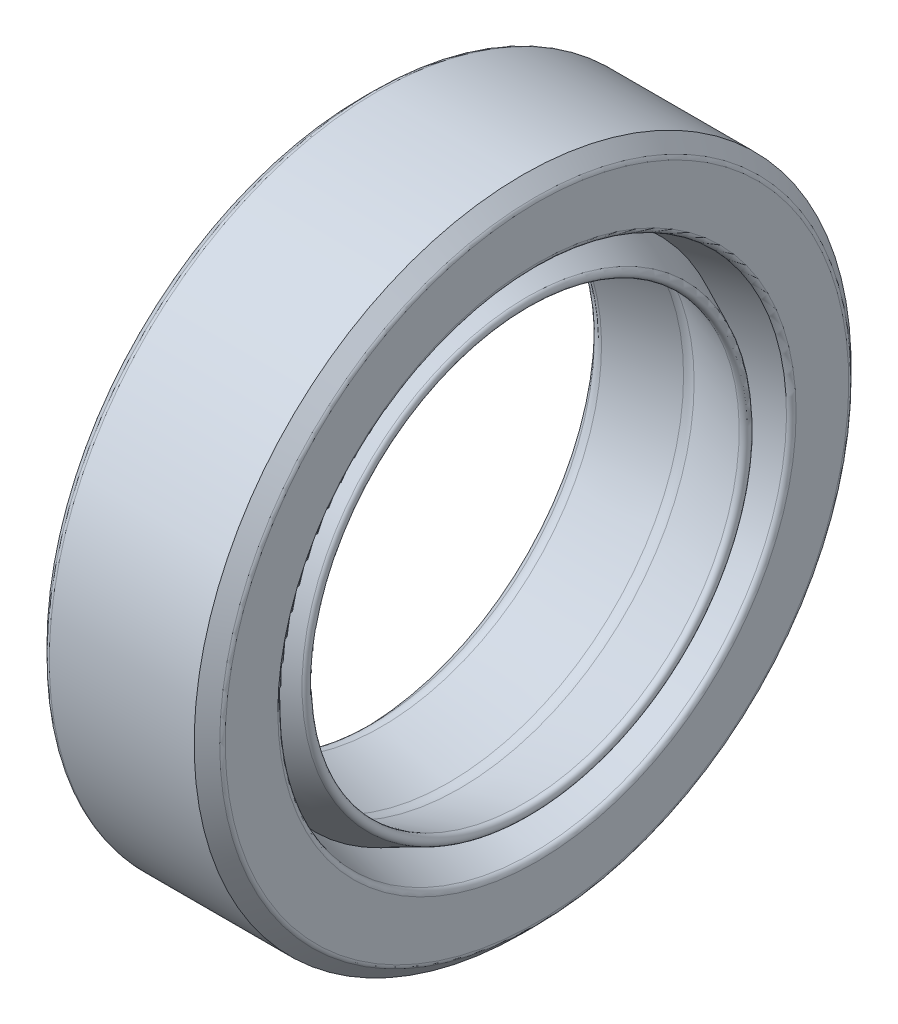
SolidWorks part; units mm, degrees
ref_plane "Front Plane" through (0, 0, 0) normal (0, 0, 1) x (1, 0, 0)
ref_plane "Top Plane" through (0, 0, 0) normal (0, 1, 0) x (1, 0, 0)
ref_plane "Right Plane" through (0, 0, 0) normal (1, 0, 0) x (0, 0, -1)
sketch "Sketch1" plane through (0, 0, 0) normal (0, 0, 1) x (1, 0, 0)
  line L0 (0, 0) -> (-7.6526, 0) construction
  line L2 (-6.8499, 12.3323) -> (-7.1853, 12.6677)
  line L3 (-7.2585, 12.8445) -> (-7.2585, 14.274)
  line L4 (-7.1853, 14.4508) -> (-6.7093, 14.9268)
  line L5 (-6.5325, 15) -> (0.0839, 15)
  line L6 (0.0839, 15) -> (0.6683, 14.4156)
  line L7 (0.7415, 14.2388) -> (0.7415, 11.8357)
  line L8 (0.5456, 11.5916) -> (-1.56, 11.125)
  line L9 (-6.83, 10.194) -> (-7.2585, 10.6224)
  line L10 (-7.2585, 10.6224) -> (-7.2585, 11.028)
  line L13 (-1.56, 11.125) -> (0.2824, 10.2714)
  line L15 (0.1243, 9.853) -> (-2.8009, 10.7213)
  line L16 (-3.3018, 10.739) -> (-6.3683, 10.0593)
  line L17 (-6.617, 12.2655) -> (-2.138, 13.2983)
  line L18 (-1.8319, 13.0547) -> (-1.8319, 12.633)
  line L19 (-2.0189, 12.391) -> (-7.2585, 11.028)
  arc A0 (0.1243, 9.853) -> (0.2824, 10.2714) centre (0.1881, 10.068) ccw
  arc A1 (-6.3683, 10.0593) -> (-6.83, 10.194) centre (-6.4765, 10.5475) cw
  arc A2 (0.7415, 14.2388) -> (0.6683, 14.4156) centre (0.4915, 14.2388) ccw
  arc A3 (0.7415, 11.8357) -> (0.5456, 11.5916) centre (0.4915, 11.8357) cw
  arc A4 (-2.0189, 12.391) -> (-1.8319, 12.633) centre (-2.0819, 12.633) ccw
  arc A5 (-1.8319, 13.0547) -> (-2.138, 13.2983) centre (-2.0819, 13.0547) ccw
  arc A6 (-6.617, 12.2655) -> (-6.8499, 12.3323) centre (-6.6732, 12.5091) cw
  arc A7 (-7.1853, 12.6677) -> (-7.2585, 12.8445) centre (-7.0085, 12.8445) cw
  arc A8 (-6.5325, 15) -> (-6.7093, 14.9268) centre (-6.5325, 14.75) ccw
  arc A9 (-7.2585, 14.274) -> (-7.1853, 14.4508) centre (-7.0085, 14.274) cw
  arc A10 (-2.8009, 10.7213) -> (-3.3018, 10.739) centre (-3.0854, 9.7626) ccw
  point P22 (-6.6361, 10)
  point P41 (-3.0491, 10.795)
  dimension "D7" = 0.5
  dimension "D8" = 0.25
  dimension "D9" = 1
  dimension "D1" = 8
  dimension "D2" = 15
  dimension "D3" = 10
  dimension "D4" = 45
  dimension "D5" = 45
  dimension "D6" = 45
revolve "Revolve1" add sketch "Sketch1" angle 360 about L0
